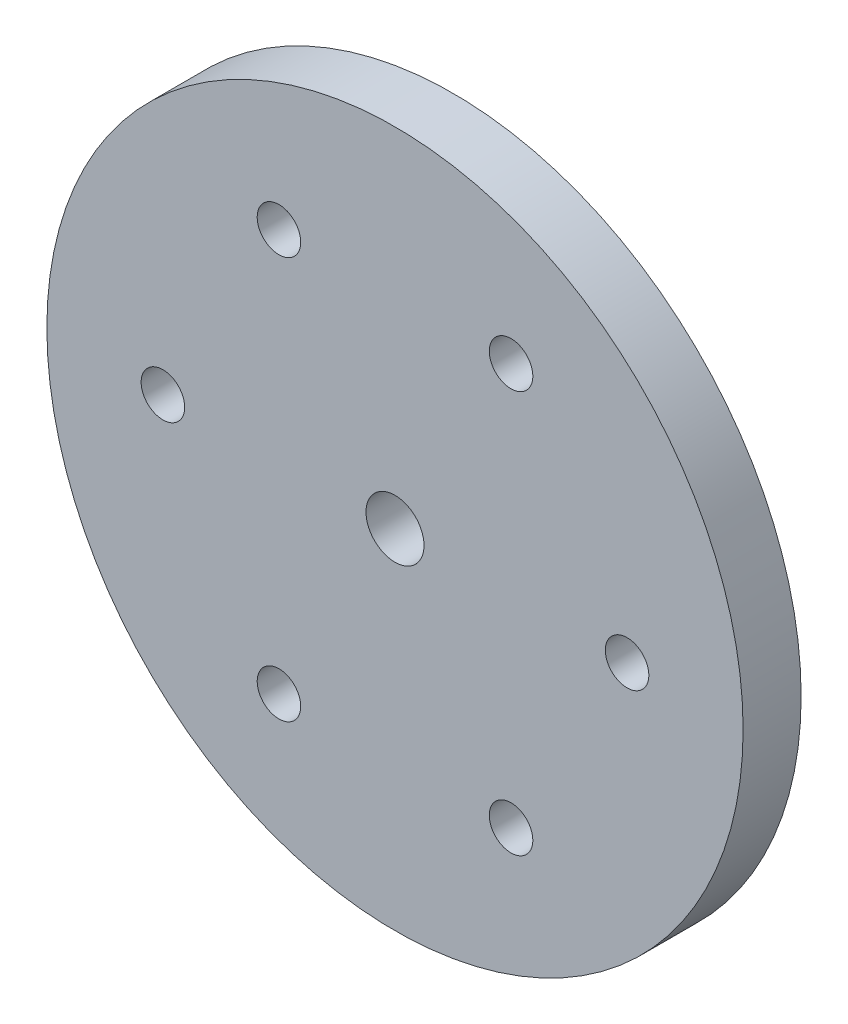
SolidWorks part; units mm, degrees
ref_plane "Front Plane" through (0, 0, 0) normal (0, 0, 1) x (1, 0, 0)
ref_plane "Top Plane" through (0, 0, 0) normal (0, 1, 0) x (1, 0, 0)
ref_plane "Right Plane" through (0, 0, 0) normal (1, 0, 0) x (0, 0, -1)
sketch "Sketch1" plane through (0, 0, 0) normal (0, 0, 1) x (1, 0, 0)
  line L0 (0, 0) -> (-25.4, 0) construction
  circle A0 centre (0, 0) radius 38.1
  circle A1 centre (0, 0) radius 25.4 construction
  point P18 (0, 0)
  dimension "D1" = 50.8
  dimension "D4" = 76.2
extrude "Boss-Extrude1" add sketch "Sketch1" along normal blind 6.35
sketch "Sketch2" plane through (0, 0, 6.35) normal (0, 0, 1) x (1, 0, 0)
  circle A1 centre (0, 0) radius 3.175
  dimension "D1" = 6.35
sketch "Sketch4" plane through (0, 0, 0) normal (0, 0, -1) x (-1, 0, 0)
  circle A0 centre (0, 0) radius 25.4 construction
  circle A1 centre (-25.4, 0) radius 2.3813
  circle A2 centre (0, 0) radius 25.4 construction
  circle A3 centre (-12.7, 21.997) radius 2.3813
  circle A4 centre (0, 0) radius 25.4 construction
  circle A5 centre (12.7, 21.997) radius 2.3813
  circle A6 centre (0, 0) radius 25.4 construction
  circle A7 centre (25.4, 0) radius 2.3813
  circle A8 centre (0, 0) radius 25.4 construction
  circle A9 centre (12.7, -21.997) radius 2.3813
  circle A10 centre (0, 0) radius 25.4 construction
  circle A11 centre (-12.7, -21.997) radius 2.3813
  point P23 (0, 0)
  dimension "D1" = 50.8
  dimension "D2" = 4.7625
  dimension "D3" = 6
extrude "Cut-Extrude2" cut sketch "Sketch4" against normal through all
extrude "Cut-Extrude3" cut sketch "Sketch2" against normal through all
